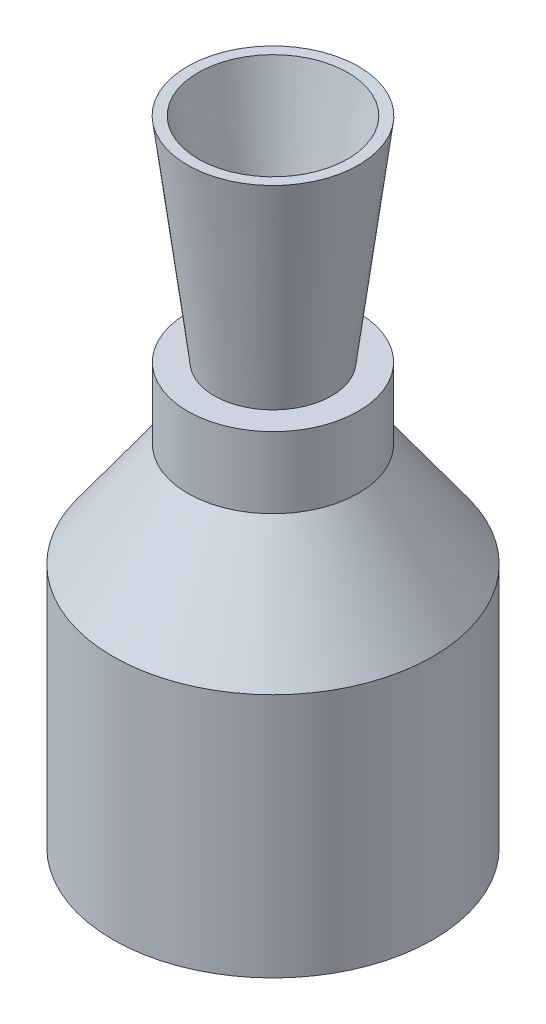
SolidWorks part; units mm, degrees
ref_plane "Front Plane" through (0, 0, 0) normal (0, 0, 1) x (1, 0, 0)
ref_plane "Top Plane" through (0, 0, 0) normal (0, 1, 0) x (1, 0, 0)
ref_plane "Right Plane" through (0, 0, 0) normal (1, 0, 0) x (0, 0, -1)
sketch "Sketch1" plane through (0, 0, 0) normal (0, 1, 0) x (1, 0, 0)
  circle A0 centre (0, 0) radius 22.5
  circle A1 centre (0, 0) radius 21
extrude "Boss-Extrude1" add sketch "Sketch1" along normal blind 34.5
sketch "Sketch5" plane through (0, 0, 0) normal (0, 0, 1) x (1, 0, 0)
  line L0 (22.5, 34.5) -> (12, 49.1202)
  line L1 (0, 0) -> (0, 50.7751) construction
  line L2 (12, 49.1202) -> (12, 59.1202)
  line L3 (21, 34.5) -> (3.5, 49.1202)
  line L4 (3.5, 49.1202) -> (3.5, 59.1202)
  line L5 (3.5, 59.1202) -> (12, 59.1202)
  line L6 (22.5, 34.5) -> (21, 34.5)
  dimension "D1" = 12
  dimension "D2" = 18
  dimension "D3" = 10
  dimension "D4" = 3.5
revolve "Revolve1" add sketch "Sketch5" angle 360 about L1
sketch "Sketch8" plane through (0, 59.1202, 0) normal (0, 1, 0) x (1, 0, 0)
  line L0 (0, 0) -> (12, 0) construction
  line L1 (0, 0) -> (0, 12) construction
ref_plane "Plane1" through (0, 0, 0) normal (0, 0, -1) x (-1, 0, 0)
sketch "Sketch10" plane through (0, 0, 0) normal (0, 0, -1) x (-1, 0, 0)
  line L0 (-3.5, 59.1202) -> (-10.5267, 89.1202)
  line L2 (-10.5267, 89.1202) -> (-12.0267, 89.1202)
  line L3 (-12.0267, 89.1202) -> (-8.25, 59.1202)
  line L4 (200000, 59.1202) -> (-200012, 59.1202) construction
  line L5 (0, 59.1202) -> (0, 74.0748) construction
  line L6 (-3.5, 59.1202) -> (-8.25, 59.1202)
  dimension "D1" = 8.25
  dimension "D2" = 30
  dimension "D3" = 1.5
revolve "Revolve3" add sketch "Sketch10" angle 360 about L5
